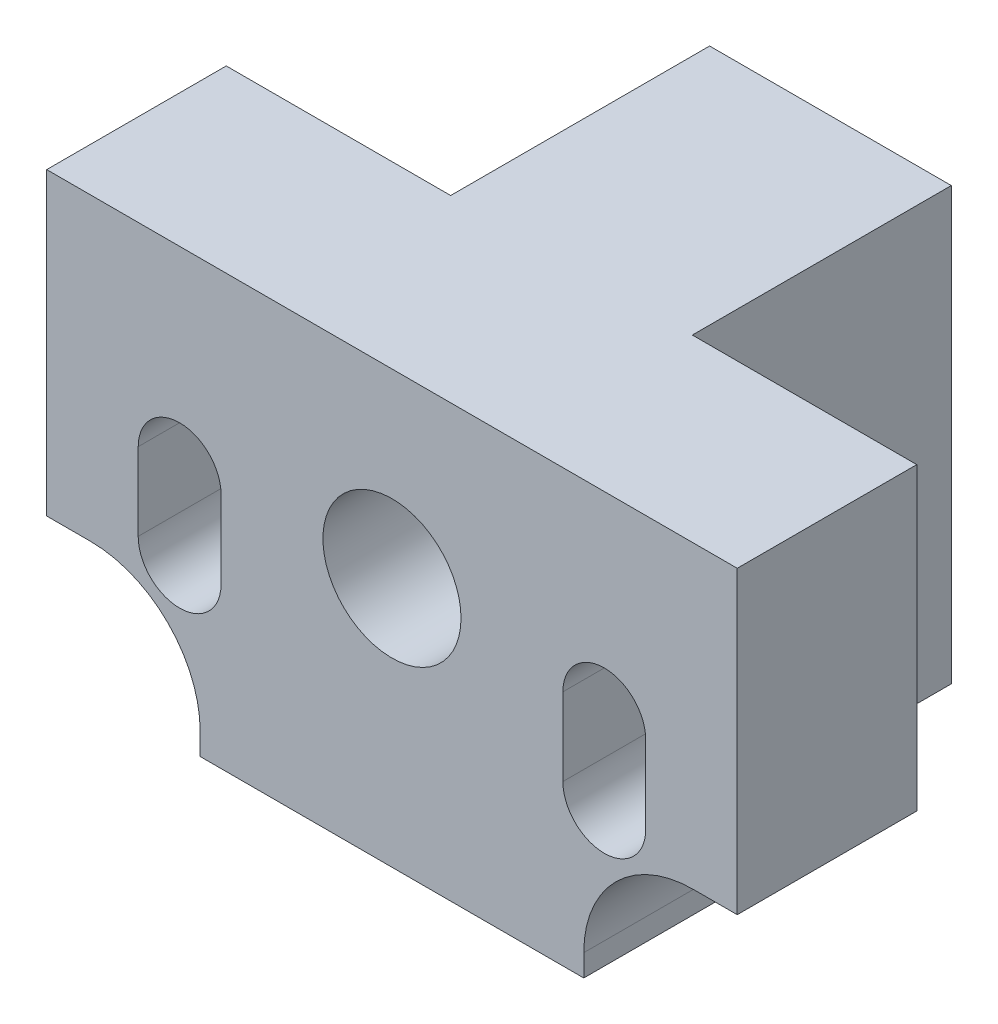
SolidWorks part; units mm, degrees
ref_plane "Front Plane" through (0, 0, 0) normal (0, 0, 1) x (1, 0, 0)
ref_plane "Top Plane" through (0, 0, 0) normal (0, 1, 0) x (1, 0, 0)
ref_plane "Right Plane" through (0, 0, 0) normal (1, 0, 0) x (0, 0, -1)
sketch "Sketch6" plane through (0, 0, 0) normal (0, 1, 0) x (1, 0, 0)
  line L0 (0, 0) -> (-20, 0)
  line L1 (-55, 0) -> (55, 0) construction
  line L2 (-20, 0) -> (-20, 10.4)
  line L3 (-20, 10.4) -> (-7, 10.4)
  line L4 (-7, 10.4) -> (-7, 25.4)
  line L5 (-7, 25.4) -> (0, 25.4)
  line L6 (0, -55) -> (0, 55) construction
  line L7 (0, 25.4) -> (0, 0)
  line L8 (151.2999, 411.6624) -> (844.6333, 411.6624) construction
  line L9 (-67.7553, 195.8919) -> (-67.7553, -497.4414) construction
  dimension "D1" = 7
  dimension "D2" = 20
  dimension "D3" = 25.4
  dimension "D4" = 15
extrude "Boss-Extrude1" add sketch "Sketch6" along normal blind 25
sketch "Sketch7" plane through (0, 0, 0) normal (0, 0, 1) x (1, 0, 0)
  line L0 (-197.1338, 72.8862) -> (-197.1338, 766.2195) construction
  line L1 (-12.3, 13.75) -> (-12.3, 9.25) construction
  line L2 (-9.9, 13.75) -> (-9.9, 9.25)
  line L3 (-14.7, 13.75) -> (-14.7, 9.25)
  line L4 (0, -13.75) -> (0, 13.75) construction
  line L5 (13.97, 0) -> (-13.97, 0) construction
  arc A0 (-9.9, 13.75) -> (-14.7, 13.75) centre (-12.3, 13.75) ccw
  arc A1 (-14.7, 9.25) -> (-9.9, 9.25) centre (-12.3, 9.25) ccw
  point P4 (-12.3, 11.5)
  dimension "D1" = 2.4
  dimension "D2" = 4.5
  dimension "D3" = 12.3
  dimension "D4" = 11.5
extrude "Cut-Extrude1" cut sketch "Sketch7" against normal through all
sketch "Sketch8" plane through (0, 0, 0) normal (0, 0, 1) x (1, 0, 0)
  line L0 (0, -13.75) -> (0, 13.75) construction
  line L1 (-20, 25) -> (0, 25) construction
  circle A0 centre (0, 14.494) radius 4
  dimension "D1" = 8
  dimension "D2" = 10.506
extrude "Cut-Extrude2" cut sketch "Sketch8" against normal through all
sketch "Sketch9" plane through (0, 0, -10.4) normal (0, 0, -1) x (-1, 0, 0)
  line L0 (11.11, 0) -> (11.11, 1.27)
  line L1 (7, 0) -> (20, 0) construction
  line L2 (17.46, 7.62) -> (20, 7.62)
  line L3 (20, 25) -> (20, 0) construction
  line L5 (11.11, 0) -> (20, 0)
  line L6 (20, 0) -> (20, 7.62)
  arc A0 (17.46, 7.62) -> (11.11, 1.27) centre (17.46, 1.27) ccw
  point P9 (11.11, 7.62)
  dimension "D3" = 6.35
  dimension "D1" = 8.89
  dimension "D2" = 7.62
extrude "Cut-Extrude3" cut sketch "Sketch9" against normal through all
mirror "Mirror1" about plane through (0, 0, 0) normal (1, 0, 0) of bodies 109 107
